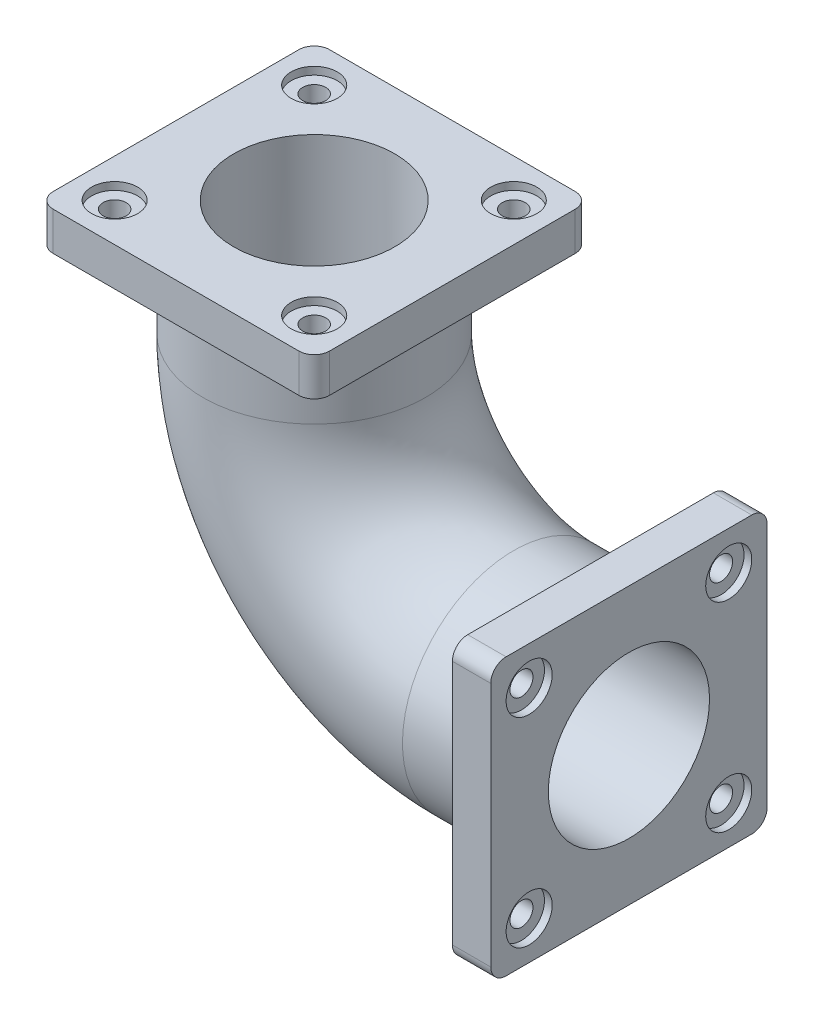
SolidWorks part; units mm, degrees
ref_plane "Front Plane" through (0, 0, 0) normal (0, 0, 1) x (1, 0, 0)
ref_plane "Top Plane" through (0, 0, 0) normal (0, 1, 0) x (1, 0, 0)
ref_plane "Right Plane" through (0, 0, 0) normal (1, 0, 0) x (0, 0, -1)
sketch "Sketch1" plane through (0, 0, 0) normal (0, 0, 1) x (1, 0, 0)
  line L0 (0, 0) -> (-150, 0)
  line L1 (-410, 260) -> (-410, 410)
  arc A0 (-150, 0) -> (-410, 260) centre (-150, 260) cw
  dimension "D3" = 260
  dimension "D1" = 150
  dimension "D2" = 150
ref_plane "Plane2" through (0, 410, 0) normal (0, 1, 0) x (1, 0, 0)
sketch "Sketch3" plane through (0, 410, 0) normal (0, 1, 0) x (1, 0, 0)
  line L0 (-410, 0) -> (-150, 0) construction
  circle A0 centre (-410, 0) radius 145
  circle A1 centre (-410, 0) radius 105
  dimension "D1" = 290
  dimension "D2" = 210
sweep "Sweep1" add profiles "Sketch3" path "Sketch1"
sketch "Sketch5" plane through (0, 410, 0) normal (0, 1, 0) x (1, 0, 0)
  line L1 (-230, 180) -> (-590, 180)
  line L2 (-230, 180) -> (-230, -180)
  line L3 (-230, -180) -> (-590, -180)
  line L4 (-590, 180) -> (-590, -180)
  line L5 (-230, 180) -> (-590, -180) construction
  line L6 (-230, -180) -> (-590, 180) construction
  point P0 (-410, 0)
  dimension "D1" = 360
  dimension "D2" = 360
extrude "Boss-Extrude1" add sketch "Sketch5" against normal blind 50
sketch "Sketch6" plane through (0, 410, 0) normal (0, 1, 0) x (1, 0, 0)
  line L0 (-410, 180) -> (-410, -180) construction
  line L1 (-230, 180) -> (-590, 180) construction
  line L2 (-590, -180) -> (-230, -180) construction
  line L3 (-590, 0) -> (-230, 0) construction
  line L4 (-590, 180) -> (-590, -180) construction
  line L5 (-230, -180) -> (-230, 180) construction
  circle A0 centre (-410, 0) radius 105
  dimension "D1" = 210
extrude "Cut-Extrude1" cut sketch "Sketch6" against normal blind 50
sketch "Sketch7" plane through (0, 410, 0) normal (0, 1, 0) x (1, 0, 0)
  line L0 (-230, 180) -> (-590, 180) construction
  line L1 (-590, 180) -> (-590, -180) construction
  line L2 (-410, 180) -> (-410, -180) construction
  line L3 (-590, -180) -> (-230, -180) construction
  line L4 (-590, 0) -> (-230, 0) construction
  line L5 (-230, -180) -> (-230, 180) construction
  circle A0 centre (-540, 130) radius 30
  circle A1 centre (-540, 130) radius 15
  circle A2 centre (-280, 130) radius 15
  circle A3 centre (-280, 130) radius 30
  circle A4 centre (-280, -130) radius 15
  circle A5 centre (-280, -130) radius 30
  circle A6 centre (-540, -130) radius 15
  circle A7 centre (-540, -130) radius 30
  dimension "D1" = 60
  dimension "D4" = 30
  dimension "D2" = 50
  dimension "D3" = 50
fillet "Fillet1" radius 20 4 edges at (-590, 385, 180) (-230, 385, 180) (-230, 385, -180) (-590, 385, -180)
ref_plane "Plane3" through (-205, 205, 0) normal (-0.7071, 0.7071, 0) x (0.7071, 0.7071, 0)
extrude "Cut-Extrude4" cut sketch "Sketch7" against normal blind 50 contours A1 | A4 | A2 | A6
sketch "Sketch9" plane through (0, 410, 0) normal (0, 1, 0) x (1, 0, 0)
  circle A0 centre (-540, -130) radius 30
  circle A1 centre (-280, -130) radius 30
  circle A2 centre (-540, 130) radius 30
  circle A3 centre (-280, 130) radius 30
extrude "Cut-Extrude5" cut sketch "Sketch9" against normal blind 10
mirror "Mirror3" about plane through (-205, 205, 0) normal (-0.7071, 0.7071, 0) of "Boss-Extrude1", "Cut-Extrude1", "Fillet1", "Cut-Extrude5", "Cut-Extrude4"
